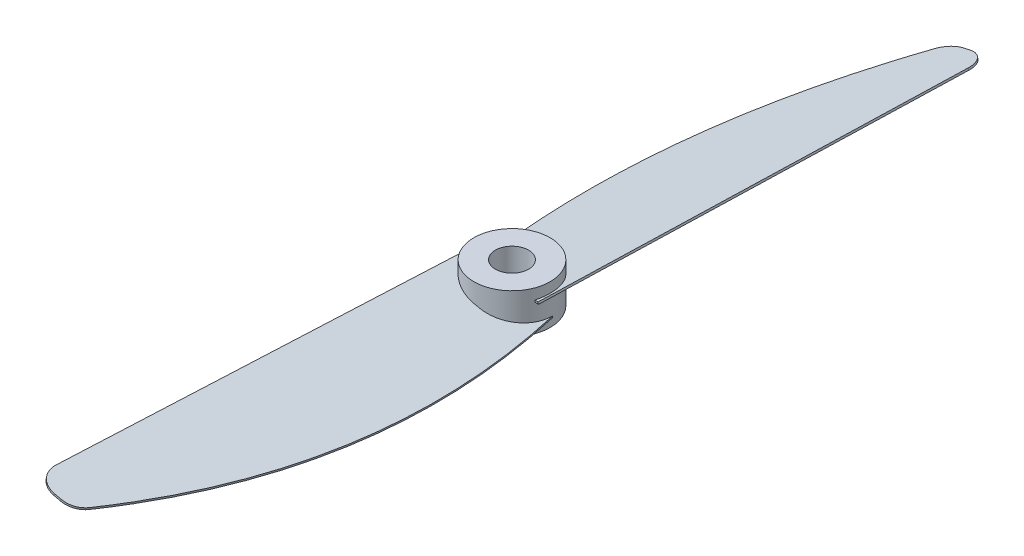
SolidWorks part; units mm, degrees
ref_plane "Front Plane" through (0, 0, 0) normal (0, 0, 1) x (1, 0, 0)
ref_plane "Top Plane" through (0, 0, 0) normal (0, 1, 0) x (1, 0, 0)
ref_plane "Right Plane" through (0, 0, 0) normal (1, 0, 0) x (0, 0, -1)
sketch "Sketch1" plane through (0, 0, 0) normal (0, 1, 0) x (1, 0, 0)
  circle A0 centre (0, 0) radius 5.75
  dimension "D1" = 11.5
extrude "Boss-Extrude1" add sketch "Sketch1" along normal mid plane 6
sketch "Sketch2" plane through (0, 0, 0) normal (0, 0, 1) x (1, 0, 0)
  line L0 (-5.75, 1.3275) -> (5.75, -1.3275)
  line L1 (-5.75, 3) -> (-5.75, -3) construction
  line L2 (5.75, -3) -> (5.75, 3) construction
  line L3 (-5.75, -3) -> (5.75, -3) construction
  dimension "D1" = 13
ref_plane "Plane1" through (0, 0, 0) normal (-0.225, -0.9744, 0) x (0.9744, -0.225, 0)
sketch "Sketch3" plane through (0, 0, 0) normal (-0.225, -0.9744, 0) x (0.9744, -0.225, 0)
  line L0 (-4.6813, -1.6866) -> (-6.2166, -2.1014)
  line L1 (-6.2166, -2.1014) -> (-8.7228, 60.3798)
  line L2 (-5.7252, 63.5) -> (-4.6544, 63.5)
  arc A0 (-8.7228, 60.3798) -> (-5.7252, 63.5) centre (-5.7252, 60.5) cw
  arc A1 (-1.973, 61.8455) -> (-4.6544, 63.5) centre (-4.6544, 60.5) ccw
  ellipse E0 centre (0.6749, 0) end of major axis (0.6749, 5.75) minor radius 5.6026 construction
  ellipse E2 centre (0.6749, 0) end of major axis (0.6749, 5.75) minor radius 5.6026
  ellipse E3 centre (0.6749, 0) end of major axis (0.6749, 5.75) minor radius 5.6026 (6.2775, 0) -> (-4.6813, -1.6866) ccw
  spline S0 degree 3 poles (6.2775, 0) (10.5945, 21.6172) (7.8326, 42.3046) (-1.973, 61.8455) knots 0 0 0 0 0.97251 0.97251 0.97251 0.97251
  dimension "D2" = 3
  dimension "D1" = 63.5
  dimension "D3" = 0
extrude "Boss-Extrude2" add sketch "Sketch3" along normal mid plane 0.3
pattern_circular "CirPattern1" count 2 over 360 about axis through (0, 3, 0) along (0, -1, 0) of "Boss-Extrude2"
sketch "Sketch4" plane through (0, -3, 0) normal (0, -1, 0) x (1, 0, 0)
  circle A0 centre (0, 0) radius 2.5
  dimension "D1" = 5
extrude "Cut-Extrude1" cut sketch "Sketch4" against normal through all
